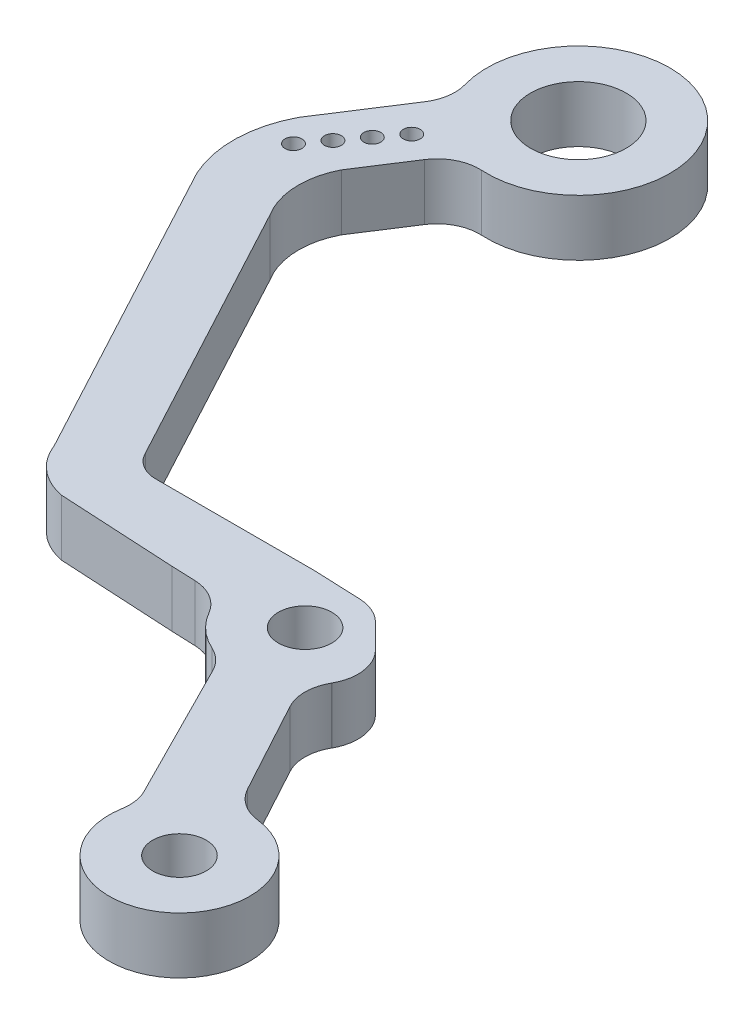
SolidWorks part; units mm, degrees
ref_plane "Front Plane" through (0, 0, 0) normal (0, 0, 1) x (1, 0, 0)
ref_plane "Top Plane" through (0, 0, 0) normal (0, 1, 0) x (1, 0, 0)
ref_plane "Right Plane" through (0, 0, 0) normal (1, 0, 0) x (0, 0, -1)
sketch "Sketch1" plane through (0, 0, 0) normal (0, 1, 0) x (1, 0, 0)
  line L0 (143.3333, 493) -> (716.6667, 493) construction
sketch "Sketch2" plane through (0, 0, 0) normal (0, 1, 0) x (1, 0, 0)
  line L0 (45.2788, 103.9326) -> (40.9177, 97.1844)
  line L1 (51.9956, 69.1217) -> (40.7298, 90.14)
  line L2 (58.0479, 69.8647) -> (65.4047, 69.8647)
  line L3 (64.0439, 65.0687) -> (56.5756, 65.4741)
  line L4 (49.0625, 100.7287) -> (45.662, 95.4669)
  line L5 (45.9135, 90.14) -> (56.2122, 70.926)
  line L6 (45.9135, 90.14) -> (45.5308, 90.8539)
  line L7 (65.4047, 69.8647) -> (69.3416, 69.8647)
  line L8 (77.3922, 49.2355) -> (71.3644, 61.1602)
  line L9 (69.3416, 69.8647) -> (73.8824, 69.6766)
  line L10 (73.8824, 69.6766) -> (77.5387, 66.0204)
  line L11 (51.9956, 69.1217) -> (52.4488, 68.2763)
  line L13 (56.9043, 65.4562) -> (55.7376, 65.5195)
  line L14 (81.2785, 52.4716) -> (75.9262, 62.3428)
  line L17 (64.0439, 65.0687) -> (67.6597, 64.927)
  circle A5 centre (72.5387, 66.0204) radius 1.9
  circle A7 centre (82.0956, 47.5388) radius 1.9
  arc A9 (45.662, 95.4669) -> (45.9135, 90.14) centre (50.4346, 93.0228) ccw
  arc A10 (41.6771, 98.3595) -> (40.7298, 90.14) centre (47.9508, 93.4721) ccw
  circle A11 centre (51.0536, 106.9163) radius 3.4
  arc A13 (52.4488, 68.2763) -> (55.7376, 65.5195) centre (56.5568, 69.837) ccw
  arc A14 (56.116, 71.1054) -> (58.0479, 69.8647) centre (58.0835, 72.0445) ccw
  arc A15 (67.6597, 64.927) -> (71.3644, 61.1602) centre (72.5387, 66.0204) ccw
  arc A16 (49.0625, 100.7287) -> (45.2788, 103.9326) centre (51.0536, 106.9163) ccw
  arc A17 (75.9262, 62.3428) -> (77.5387, 66.0204) centre (72.5387, 66.0204) ccw
  arc A19 (77.3922, 49.2355) -> (81.2785, 52.4716) centre (82.0956, 47.5388) ccw
extrude "Boss-Extrude1" add sketch "Sketch2" along normal blind 4
sketch "Sketch3" plane through (0, 4, 0) normal (0, 1, 0) x (1, 0, 0)
  circle A0 centre (42.3534, 95.379) radius 0.6
  circle A1 centre (43.5576, 96.9758) radius 0.6
  circle A2 centre (44.7618, 98.5727) radius 0.6
  circle A3 centre (45.9659, 100.1695) radius 0.6
extrude "Cut-Extrude1" cut sketch "Sketch3" against normal blind 6
fillet "Fillet1" radius 3 9 edges at (77.5387, 2, -66.0204) (73.8824, 2, -69.6766) (75.9262, 2, -62.3428) (77.3922, 2, -49.2355) (81.2785, 2, -52.4716) (71.3644, 2, -61.1602) (67.6597, 2, -64.927) (45.2788, 2, -103.9326) (49.0625, 2, -100.7287)
